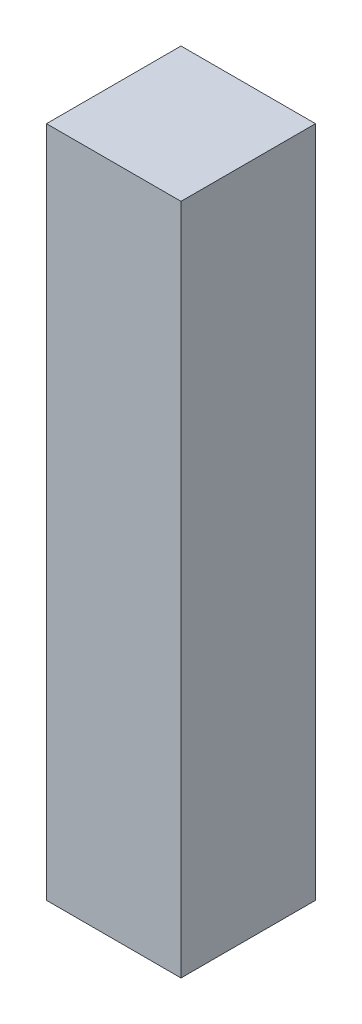
SolidWorks part; units mm, degrees
ref_plane "Front Plane" through (0, 0, 0) normal (0, 0, 1) x (1, 0, 0)
ref_plane "Top Plane" through (0, 0, 0) normal (0, 1, 0) x (1, 0, 0)
ref_plane "Right Plane" through (0, 0, 0) normal (1, 0, 0) x (0, 0, -1)
sketch "Sketch2" plane through (0, 0, 0) normal (0, 1, 0) x (1, 0, 0)
  line L1 (-0.5, 0.5) -> (0.5, 0.5)
  line L2 (-0.5, 0.5) -> (-0.5, -0.5)
  line L3 (-0.5, -0.5) -> (0.5, -0.5)
  line L4 (0.5, 0.5) -> (0.5, -0.5)
  line L5 (-0.5, 0.5) -> (0.5, -0.5) construction
  line L6 (-0.5, -0.5) -> (0.5, 0.5) construction
  point P0 (0, 0)
  dimension "D1" = 1
extrude "Boss-Extrude1" add sketch "Sketch2" along normal blind 5
